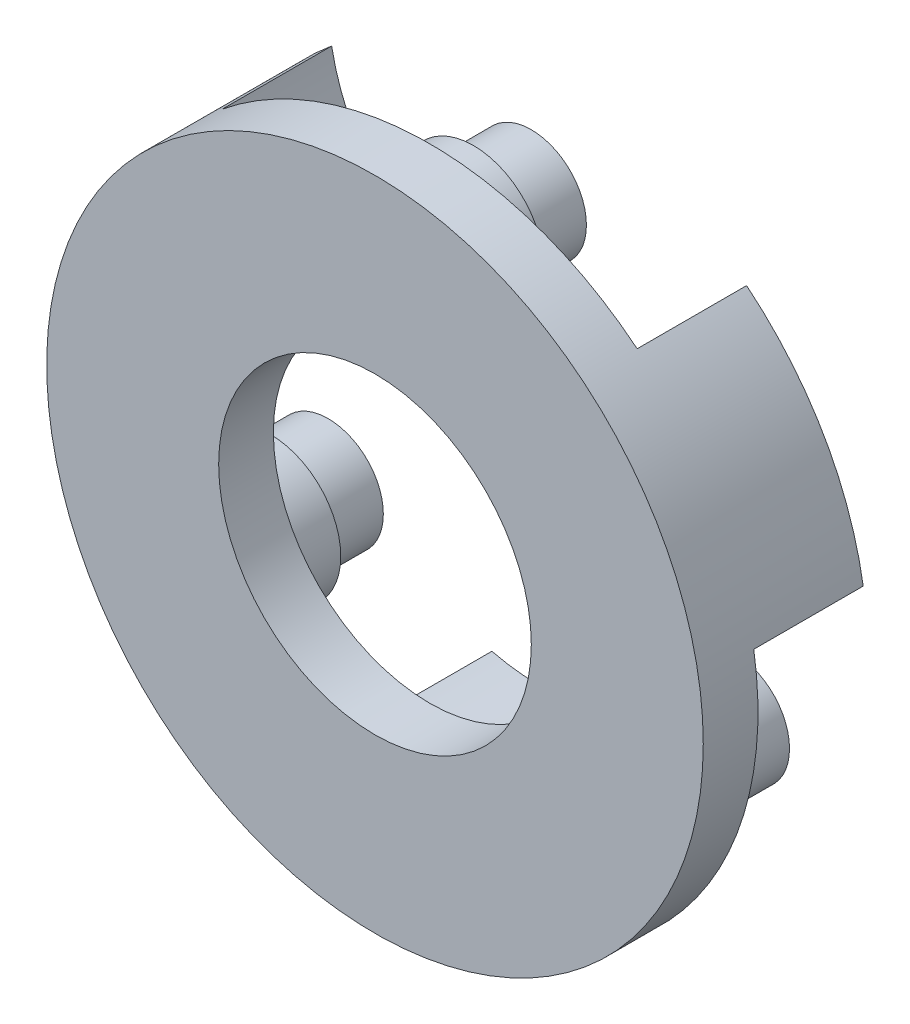
SolidWorks part; units mm, degrees
ref_plane "Front Plane" through (0, 0, 0) normal (0, 0, 1) x (1, 0, 0)
ref_plane "Top Plane" through (0, 0, 0) normal (0, 1, 0) x (1, 0, 0)
ref_plane "Right Plane" through (0, 0, 0) normal (1, 0, 0) x (0, 0, -1)
sketch "Sketch1" plane through (0, 0, 0) normal (0, 0, 1) x (1, 0, 0)
  circle A0 centre (0, 0) radius 21
  dimension "D1" = 42
extrude "Boss-Extrude1" add sketch "Sketch1" along normal blind 3.5 contours A0
sketch "Sketch3" plane through (0, 0, 0) normal (0, 0, -1) x (-1, 0, 0)
  line L0 (0, 7.5) -> (0, 18.75) construction
  arc A4 (-7.459, -19.6307) -> (-3.0219, -12.1292) centre (-16.238, -9.375) ccw
  arc A5 (-13.2712, 16.275) -> (-8.9933, 8.6817) centre (0, 18.75) ccw
  arc A6 (20.7302, 3.3557) -> (12.0152, 3.4476) centre (16.238, -9.375) ccw
  circle A7 centre (0, 0) radius 12.5
  arc A9 (8.9933, 8.6817) -> (13.2712, 16.275) centre (0, 18.75) ccw
  arc A10 (-12.0152, 3.4476) -> (-20.7302, 3.3557) centre (-16.238, -9.375) ccw
  arc A11 (-13.2712, 16.275) -> (-20.7302, 3.3557) centre (0, 0) ccw
  arc A12 (-7.459, -19.6307) -> (7.459, -19.6307) centre (0, 0) ccw
  arc A13 (20.7302, 3.3557) -> (13.2712, 16.275) centre (0, 0) ccw
  arc A14 (3.0219, -12.1292) -> (7.459, -19.6307) centre (16.238, -9.375) ccw
  point P13 (0, 0)
  point P19 (0, 0)
  dimension "D1" = 42
  dimension "D2" = 11.25
  dimension "D5" = 27
  dimension "D7" = 25
  dimension "D6" = 3
sketch "Sketch4" plane through (0, 0, 0) normal (0, 0, -1) x (-1, 0, 0)
  circle A0 centre (0, 0) radius 10
  dimension "D1" = 20
extrude "Cut-Extrude1" cut sketch "Sketch4" against normal blind 8.2
sketch "Sketch11" plane through (0, 0, 0) normal (0, 0, -1) x (-1, 0, 0)
  line L0 (0, 0) -> (0, 15) construction
  line L1 (0, 7.5) -> (0, 18.75) construction
  circle A0 centre (0, 15) radius 1.5
  circle A1 centre (12.9904, -7.5) radius 1.5
  circle A2 centre (-12.9904, -7.5) radius 1.5
  point P12 (0, 0)
  dimension "D2" = 3
  dimension "D3" = 3
  dimension "D1" = 15
extrude "Cut-Extrude2" cut sketch "Sketch11" against normal blind 10
extrude "Boss-Extrude2" add sketch "Sketch3" along normal blind 7 contours A10 A7 A5 L0 | A9 A7 A6 L0 | A14 A7 A4 L0
sketch "Sketch14" plane through (0, 0, -7) normal (0, 0, -1) x (-1, 0, 0)
  line L0 (18.1865, 10.5) -> (0, 0) construction
  line L1 (0, 0) -> (13.8564, 8) construction
  arc A0 (20.7302, 3.3557) -> (13.2712, 16.275) centre (0, 0) ccw construction
  circle A1 centre (13.8564, 8) radius 1.5
  circle A2 centre (0, -16) radius 1.5
  circle A3 centre (-13.8564, 8) radius 1.5
  point P14 (0, 0)
  dimension "D2" = 3
  dimension "D1" = 16
  dimension "D3" = 3
extrude "Cut-Extrude3" cut sketch "Sketch14" against normal blind 5
sketch "Sketch16" plane through (0, 0, 3.5) normal (0, 0, 1) x (1, 0, 0)
  circle A0 centre (0, 15) radius 3.525
  circle A1 centre (12.9904, -7.5) radius 3.525
  circle A2 centre (-12.9904, -7.5) radius 3.525
  point P9 (0, 0)
  dimension "D1" = 7.05
  dimension "D2" = 3
extrude "Boss-Extrude3" add sketch "Sketch16" against normal blind 10
sketch "Sketch17" plane through (0, 0, 0) normal (0, 0, -1) x (-1, 0, 0)
  circle A0 centre (0, 15) radius 4.5
  circle A1 centre (12.9904, -7.5) radius 4.5
  circle A2 centre (-12.9904, -7.5) radius 4.5
  point P9 (0, 0)
  dimension "D1" = 9
  dimension "D2" = 3
extrude "Boss-Extrude4" add sketch "Sketch17" along normal blind 2.8
